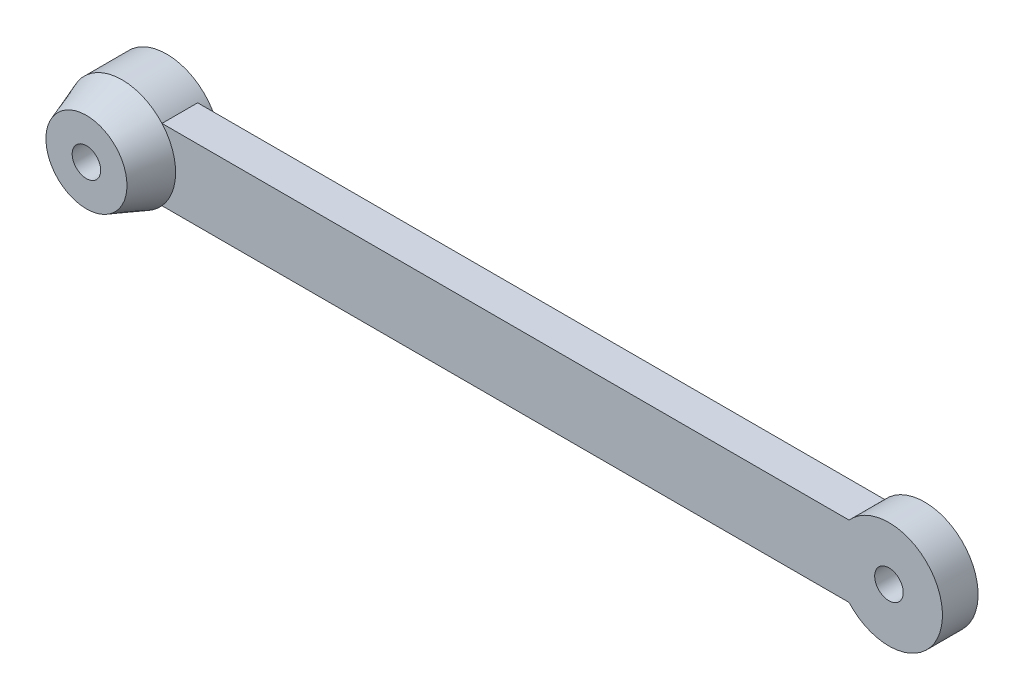
SolidWorks part; units mm, degrees
ref_plane "Ön Düzlem" through (0, 0, 0) normal (0, 0, 1) x (1, 0, 0)
ref_plane "Üst Düzlem" through (0, 0, 0) normal (0, 1, 0) x (1, 0, 0)
ref_plane "Sağ Düzlem" through (0, 0, 0) normal (1, 0, 0) x (0, 0, -1)
sketch "Sketch1" plane through (0, 0, 0) normal (0, 0, 1) x (1, 0, 0)
  line L0 (8.2916, 12.5) -> (206.7084, 12.5)
  line L1 (8.2916, -12.5) -> (206.7084, -12.5)
  circle A0 centre (0, 0) radius 15
  circle A1 centre (215, 0) radius 15
  dimension "D1" = 30
  dimension "D3" = 30
  dimension "D2" = 25
  dimension "D4" = 215
  dimension "D5" = 12.5
extrude "Boss-Extrude1" add sketch "Sketch1" along normal blind 10 contours A0 | A1
sketch "Sketch2" plane through (0, 0, 10) normal (0, 0, 1) x (1, 0, 0)
  circle A1 centre (0, 0) radius 15
  circle A2 centre (0, 0) radius 15
  dimension "D1" = 0
extrude "Boss-Extrude2" add sketch "Sketch2" along normal blind 10 draft 20
sketch "Sketch5" plane through (0, 0, 0) normal (0, 0, 1) x (1, 0, 0)
  line L0 (11.1803, 10) -> (203.8197, 10)
  line L1 (203.8197, -10) -> (11.1803, -10)
  circle A0 centre (0, 0) radius 15 construction
  circle A1 centre (215, 0) radius 15 construction
  circle A2 centre (0, 0) radius 15
  circle A3 centre (215, 0) radius 15
  dimension "D1" = 20
  dimension "D2" = 10
extrude "Boss-Extrude3" add sketch "Sketch5" along normal blind 5 contours A3 L0 A2 L1
sketch "Sketch6" plane through (0, 0, 5) normal (0, 0, 1) x (1, 0, 0)
  circle A1 centre (0, 0) radius 15 construction
  arc A3 (14.7902, -2.5) -> (14.7902, 2.5) centre (0, 0) ccw
extrude "Boss-Extrude4" add sketch "Sketch6" along normal blind 5
sketch "Sketch13" plane through (0, 0, 0) normal (0, 0, -1) x (-1, 0, 0)
  circle A0 centre (-215, 0) radius 4
  circle A1 centre (0, 0) radius 4
extrude "Cut-Extrude1" cut sketch "Sketch13" against normal blind 20
sketch "Sketch14" plane through (0, 0, 0) normal (0, 0, -1) x (-1, 0, 0)
  circle A0 centre (0, 0) radius 4
  circle A1 centre (0, 0) radius 15
extrude "Boss-Extrude7" add sketch "Sketch14" along normal blind 2.5
scale "Echelle1" scale about centroid uniform scaling yes scale factor 0.6
